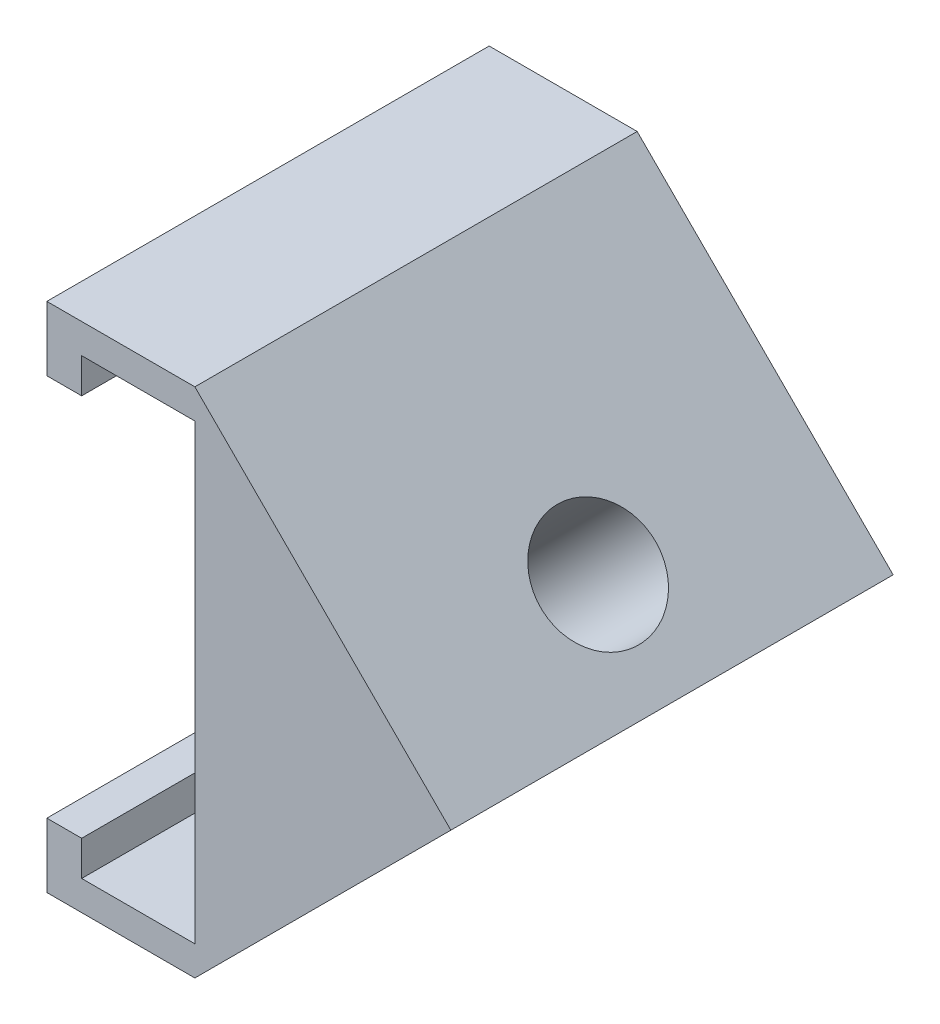
SolidWorks part; units mm, degrees
ref_plane "Front Plane" through (0, 0, 0) normal (0, 0, 1) x (1, 0, 0)
ref_plane "Top Plane" through (0, 0, 0) normal (0, 1, 0) x (1, 0, 0)
ref_plane "Right Plane" through (0, 0, 0) normal (1, 0, 0) x (0, 0, -1)
sketch "Sketch1" plane through (0, 0, 0) normal (0, 0, 1) x (1, 0, 0)
  line L0 (-7.35, 7.35) -> (0, 0)
  line L1 (-11.6, 7.35) -> (-7.35, 7.35)
  line L2 (-11.6, 7.35) -> (-11.6, 6.5)
  line L3 (-11.6, -7.35) -> (-7.35, -7.35)
  line L7 (0, 0) -> (-7.35, -7.35)
  line L12 (-7.35, 6.5) -> (-7.35, -6.5)
  line L13 (-11.6, -6.5) -> (-11.6, -7.35)
  line L14 (0, 0) -> (-7.35, 0) construction
  line L16 (-11.6, -6.5) -> (-11.6, -5.5)
  line L17 (-11.6, -5.5) -> (-10.6, -5.5)
  line L18 (-10.6, -6.5) -> (-10.6, -5.5)
  line L19 (-11.6, 5.5) -> (-10.6, 5.5)
  line L20 (-10.6, 6.5) -> (-10.6, 5.5)
  line L22 (-11.6, 6.5) -> (-11.6, 5.5)
  line L23 (-10.6, 6.5) -> (-7.35, 6.5)
  line L24 (-10.6, -6.5) -> (-7.35, -6.5)
  line L25 (-7.35, 7.35) -> (-7.35, -7.35) construction
  dimension "D1" = 14.7
  dimension "D2" = 4.25
  dimension "D3" = 4.25
  dimension "D4" = 13
  dimension "D5" = 3.25
  dimension "D6" = 1
  dimension "D7" = 225
extrude "Boss-Extrude1" add sketch "Sketch1" along normal blind 12.7
sketch "Sketch7" plane through (0, 0, 0) normal (0.7071, 0.7071, 0) x (0, 0, -1)
  line L0 (-12.7, 0) -> (0, 0) construction
  line L1 (-6.35, 10.3945) -> (-6.35, 0) construction
  line L2 (-12.7, 10.3945) -> (0, 10.3945) construction
  circle A0 centre (-6.35, 3) radius 1.65
  dimension "D1" = 3.3
  dimension "D2" = 3
extrude "Cut-Extrude2" cut sketch "Sketch7" against normal blind 5
